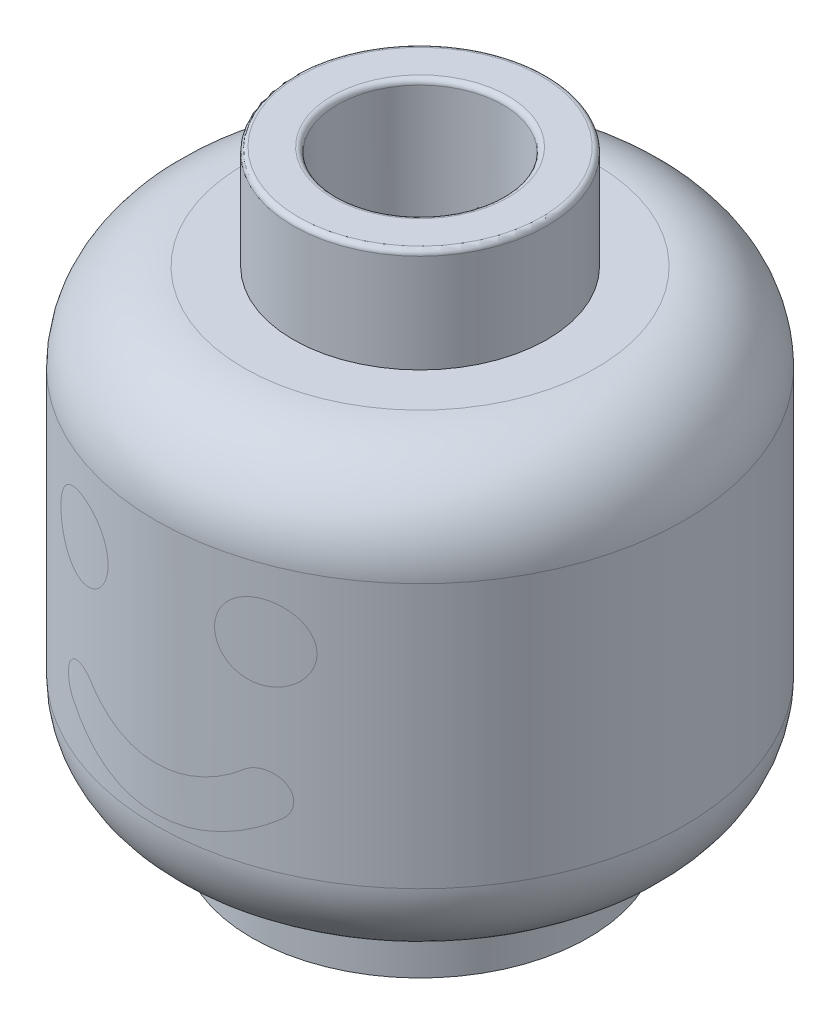
SolidWorks part; units mm, degrees
ref_plane "Front Plane" through (0, 0, 0) normal (0, 0, 1) x (1, 0, 0)
ref_plane "Top Plane" through (0, 0, 0) normal (0, 1, 0) x (1, 0, 0)
ref_plane "Right Plane" through (0, 0, 0) normal (1, 0, 0) x (0, 0, -1)
sketch "Sketch2" plane through (0, 0, 0) normal (0, 1, 0) x (1, 0, 0)
  circle A0 centre (0, 0) radius 5.1
  dimension "D1" = 10.2
extrude "Boss-Extrude1" add sketch "Sketch2" along normal blind 8.5
sketch "Sketch3" plane through (0, 8.5, 0) normal (0, 1, 0) x (1, 0, 0)
  circle A2 centre (0, 0) radius 2.45
  dimension "D2" = 4.9
extrude "Boss-Extrude2" add sketch "Sketch3" along normal blind 2 contours A2
sketch "Sketch4" plane through (0, 10.5, 0) normal (0, 1, 0) x (1, 0, 0)
  circle A0 centre (0, 0) radius 1.6
  dimension "D1" = 3.2
extrude "Cut-Extrude1" cut sketch "Sketch4" against normal blind 2 contours A0
fillet "Fillet1" radius 1.7 2 edges at (0, 0, 5.1) (0, 8.5, 5.1)
fillet "Fillet2" radius 0.1 2 edges at (0, 10.5, 1.6) (0, 10.5, 2.45)
sketch "Sketch5" plane through (0, 0, 0) normal (0, -1, 0) x (1, 0, 0)
  circle A0 centre (0, 0) radius 3.25
  dimension "D1" = 6.5
extrude "Boss-Extrude3" add sketch "Sketch5" along normal blind 1.1
sketch "Sketch6" plane through (0, -1.1, 0) normal (0, -1, 0) x (1, 0, 0)
  circle A0 centre (0, 0) radius 2.45
  dimension "D1" = 4.9
extrude "Cut-Extrude2" cut sketch "Sketch6" against normal blind 8.5
ref_plane "Plane3" through (0, 8.5, 0) normal (0, 1, 0) x (1, 0, 0)
sketch "Sketch11" plane through (0, 8.5, 0) normal (0, 1, 0) x (1, 0, 0)
  line L0 (0, 0) -> (0, -5.9398) construction
  line L1 (0, 0) -> (0, 5.6442) construction
  line L2 (0, 0) -> (6.6013, 0) construction
  line L3 (0, 0) -> (-8.0229, 0) construction
  line L4 (-0.42, 1.5439) -> (-0.42, 0.2406)
  line L5 (0.42, 1.5439) -> (0.42, 0.2406)
  line L6 (-0.42, 0.2406) -> (-1.5466, -0.4098)
  line L7 (0, -0.4869) -> (-1.1258, -1.1369)
  line L8 (0, -0.4869) -> (1.1258, -1.1369)
  line L9 (0.42, 0.2406) -> (1.5466, -0.4098)
  circle A0 centre (0, 0) radius 1.6 construction
  circle A1 centre (0, 0) radius 1.6
  dimension "D12" = 3.2
  dimension "D1" = 0.42
  dimension "D2" = 0.42
  dimension "D3" = 0.84
  dimension "D4" = 0.84
  dimension "D5" = 120
  dimension "D6" = 120
  dimension "D7" = 1.3033
  dimension "D8" = 1.3009
  dimension "D9" = 1.3
  dimension "D10" = 1.3
  dimension "D11" = 1.3033
extrude "Cut-Extrude3" cut sketch "Sketch11" against normal blind 1.1 contours L4 A1 L6 | L9 A1 L5 | L7 A1 L8
ref_plane "Plane5" through (0, 0, -5.1) normal (0, 0, 1) x (1, 0, 0)
sketch "Sketch13" plane through (0, 0, -5.1) normal (0, 0, 1) x (1, 0, 0)
  line L0 (0, 0) -> (0, 10.9801) construction
  line L1 (0, 5.49) -> (-8.2535, 5.49) construction
  line L2 (0, 5.49) -> (7.6097, 5.49) construction
  line L3 (0, 2.3178) -> (8.5625, 2.3178) construction
  line L4 (0, 2.3178) -> (-6.5627, 2.3178) construction
  circle A0 centre (-1.75, 5.49) radius 0.7219
  circle A1 centre (1.75, 5.49) radius 0.7219
  arc A2 (-1.75, 2.9429) -> (1.75, 2.9429) centre (0, 5.0799) ccw construction
  arc A3 (-2.0191, 2.6143) -> (2.0191, 2.6143) centre (0, 5.0799) ccw
  arc A4 (-1.4809, 3.2715) -> (1.4809, 3.2715) centre (0, 5.0799) ccw
  arc A5 (-1.4809, 3.2715) -> (-2.0191, 2.6143) centre (-1.75, 2.9429) ccw
  arc A6 (2.0191, 2.6143) -> (1.4809, 3.2715) centre (1.75, 2.9429) ccw
  point P13 (0, 2.3178)
  dimension "D1" = 1.4438
  dimension "D6" = 1.4438
  dimension "D2" = 1.75
  dimension "D3" = 2.5472
  dimension "D4" = 2.5472
  dimension "D5" = 3.1723
split line "Split Line1"
